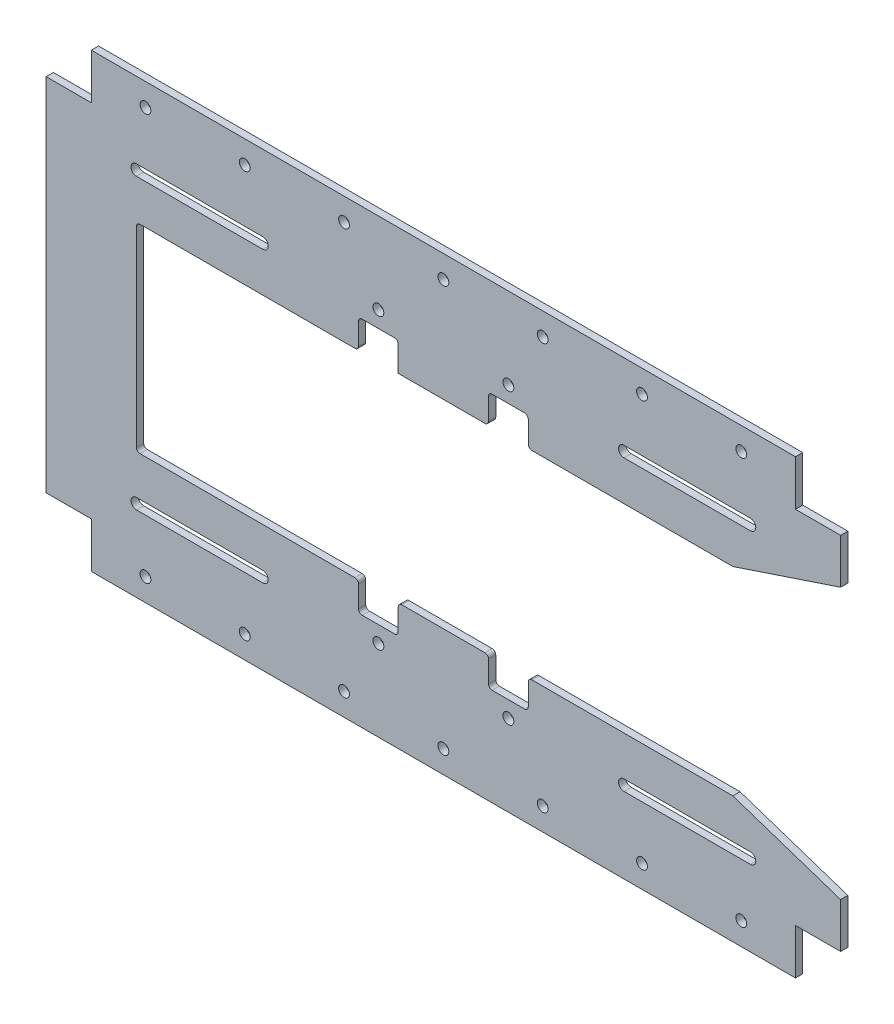
SolidWorks part; units mm, degrees
ref_plane "Front Plane" through (0, 0, 0) normal (0, 0, 1) x (1, 0, 0)
ref_plane "Top Plane" through (0, 0, 0) normal (0, 1, 0) x (1, 0, 0)
ref_plane "Right Plane" through (0, 0, 0) normal (1, 0, 0) x (0, 0, -1)
sketch "Model" plane through (0, 0, 0) normal (0, 0, 1) x (1, 0, 0)
  line L0 (220, -99.8) -> (220, -74.9)
  line L1 (220, -74.9) -> (160.3, -55)
  line L2 (160.3, -55) -> (49, -55)
  line L3 (47, -57) -> (47, -69)
  line L4 (45, -71) -> (27, -71)
  line L5 (25, -69) -> (25, -57)
  line L6 (23, -55) -> (-23, -55)
  line L7 (-25, -57) -> (-25, -69)
  line L8 (-27, -71) -> (-45, -71)
  line L9 (-47, -69) -> (-47, -57)
  line L10 (-49, -55) -> (-168, -55)
  line L11 (-170, -53) -> (-170, 53)
  line L12 (-168, 55) -> (-49, 55)
  line L13 (-47, 57) -> (-47, 69)
  line L14 (-45, 71) -> (-27, 71)
  line L15 (-25, 69) -> (-25, 55)
  line L16 (-25, 55) -> (23, 55)
  line L17 (25, 57) -> (25, 69)
  line L18 (27, 71) -> (45, 71)
  line L19 (47, 69) -> (47, 57)
  line L20 (49, 55) -> (160.3, 55)
  line L21 (160.3, 55) -> (220, 74.9)
  line L22 (220, 74.9) -> (220, 99.8)
  line L23 (220, 99.8) -> (195, 99.8)
  line L24 (195, 99.8) -> (195, 125)
  line L25 (195, 125) -> (-195, 125)
  line L26 (-195, 125) -> (-195, 99.8)
  line L27 (-195, 99.8) -> (-220, 99.8)
  line L28 (-220, 99.8) -> (-220, -99.8)
  line L29 (-220, -99.8) -> (-195, -99.8)
  line L30 (-195, -99.8) -> (-195, -125)
  line L31 (-195, -125) -> (195, -125)
  line L32 (195, -125) -> (195, -99.8)
  line L33 (195, -99.8) -> (220, -99.8)
  line L34 (170, -83) -> (100, -83)
  line L35 (100, -77) -> (170, -77)
  line L36 (-170, -77) -> (-100, -77)
  line L37 (-100, -83) -> (-170, -83)
  line L38 (170, 77) -> (100, 77)
  line L39 (100, 83) -> (170, 83)
  line L40 (-170, 83) -> (-100, 83)
  line L41 (-100, 77) -> (-170, 77)
  circle A0 centre (36, 80) radius 3
  circle A1 centre (-36, -80) radius 3
  circle A2 centre (-36, 80) radius 3
  circle A3 centre (36, -80) radius 3
  circle A4 centre (55, 112.5) radius 3
  circle A5 centre (-110, 112.5) radius 3
  circle A6 centre (-55, 112.5) radius 3
  circle A7 centre (0, 112.5) radius 3
  circle A8 centre (-165, 112.5) radius 3
  circle A9 centre (110, 112.5) radius 3
  circle A10 centre (165, 112.5) radius 3
  circle A11 centre (110, -112.5) radius 3
  circle A12 centre (-165, -112.5) radius 3
  circle A13 centre (0, -112.5) radius 3
  circle A14 centre (-55, -112.5) radius 3
  circle A15 centre (-110, -112.5) radius 3
  circle A16 centre (55, -112.5) radius 3
  circle A17 centre (165, -112.5) radius 3
  arc A18 (49, -55) -> (47, -57) centre (49, -57) ccw
  arc A19 (45, -71) -> (47, -69) centre (45, -69) ccw
  arc A20 (25, -69) -> (27, -71) centre (27, -69) ccw
  arc A21 (25, -57) -> (23, -55) centre (23, -57) ccw
  arc A22 (-23, -55) -> (-25, -57) centre (-23, -57) ccw
  arc A23 (-27, -71) -> (-25, -69) centre (-27, -69) ccw
  arc A24 (-47, -69) -> (-45, -71) centre (-45, -69) ccw
  arc A25 (-47, -57) -> (-49, -55) centre (-49, -57) ccw
  arc A26 (-170, -53) -> (-168, -55) centre (-168, -53) ccw
  arc A27 (-168, 55) -> (-170, 53) centre (-168, 53) ccw
  arc A28 (-49, 55) -> (-47, 57) centre (-49, 57) ccw
  arc A29 (-45, 71) -> (-47, 69) centre (-45, 69) ccw
  arc A30 (-25, 69) -> (-27, 71) centre (-27, 69) ccw
  arc A31 (23, 55) -> (25, 57) centre (23, 57) ccw
  arc A32 (27, 71) -> (25, 69) centre (27, 69) ccw
  arc A33 (47, 69) -> (45, 71) centre (45, 69) ccw
  arc A34 (47, 57) -> (49, 55) centre (49, 57) ccw
  arc A35 (100, -77) -> (100, -83) centre (100, -80) ccw
  arc A36 (170, -83) -> (170, -77) centre (170, -80) ccw
  arc A37 (-170, -77) -> (-170, -83) centre (-170, -80) ccw
  arc A38 (-100, -83) -> (-100, -77) centre (-100, -80) ccw
  arc A39 (170, 77) -> (170, 83) centre (170, 80) ccw
  arc A40 (100, 83) -> (100, 77) centre (100, 80) ccw
  arc A41 (-170, 83) -> (-170, 77) centre (-170, 80) ccw
  arc A42 (-100, 77) -> (-100, 83) centre (-100, 80) ccw
extrude "Boss-Extrude1" add sketch "Model" along normal blind 4
ref_plane "Plane1" through (0, 0, 0) normal (0, -1, 0) x (-1, 0, 0)
ref_plane "Plane2" through (0, 0, 0) normal (-1, 0, 0) x (0, 1, 0)
